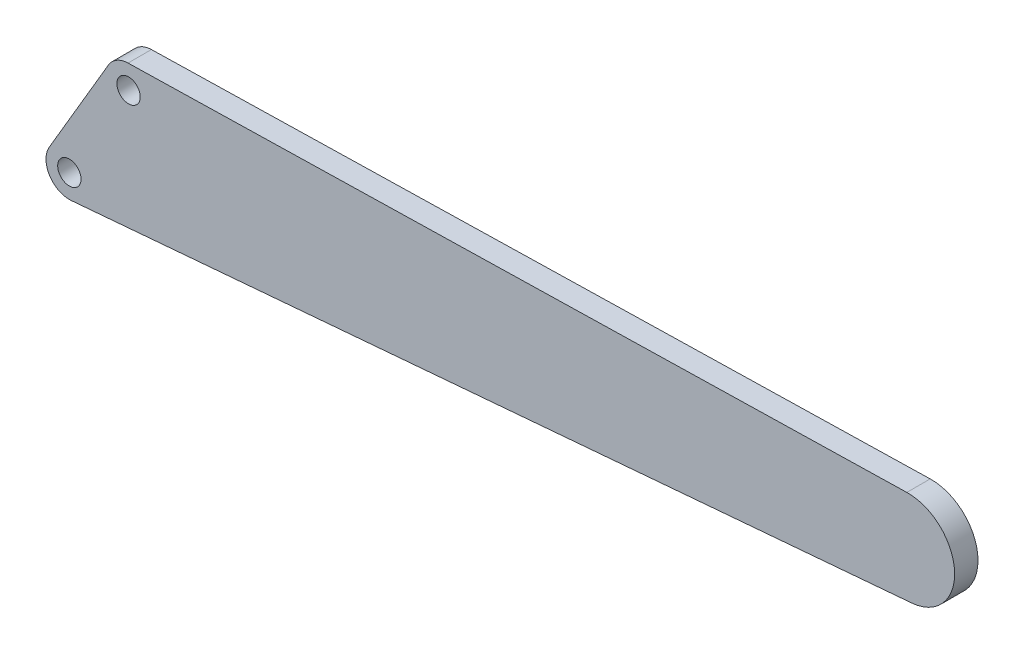
SolidWorks part; units mm, degrees
ref_plane "Front Plane" through (0, 0, 0) normal (0, 0, 1) x (1, 0, 0)
ref_plane "Top Plane" through (0, 0, 0) normal (0, 1, 0) x (1, 0, 0)
ref_plane "Right Plane" through (0, 0, 0) normal (1, 0, 0) x (0, 0, -1)
sketch "Sketch2" plane through (0, 0, 0) normal (0, 0, 1) x (1, 0, 0)
  line L0 (-7.5968, -12.934) -> (0, 0)
  line L1 (0, 0) -> (100, -0.7468)
  dimension "D1" = 100
  dimension "D2" = 15
  dimension "D3" = 120
sketch "Sketch3" plane through (0, 0, 0) normal (0, 0, 1) x (1, 0, 0)
  line L0 (-10.1836, -11.4147) -> (-2.5868, 1.5194)
  line L1 (-0.0676, 2.9992) -> (99.8648, 5.2517)
  line L2 (100.5099, -6.7251) -> (-7.3419, -15.9232)
  circle A0 centre (-7.5968, -12.934) radius 1.5
  arc A1 (-10.1836, -11.4147) -> (-7.3419, -15.9232) centre (-7.5968, -12.934) ccw
  circle A2 centre (0, 0) radius 1.5
  arc A3 (-0.0676, 2.9992) -> (-2.5868, 1.5194) centre (0, 0) ccw
  arc A4 (100.5099, -6.7251) -> (99.8648, 5.2517) centre (100, -0.7468) ccw
  dimension "D1" = 3
  dimension "D2" = 6
  dimension "D3" = 3
  dimension "D4" = 6
  dimension "D5" = 12
extrude "Boss-Extrude1" add sketch "Sketch3" along normal blind 3
